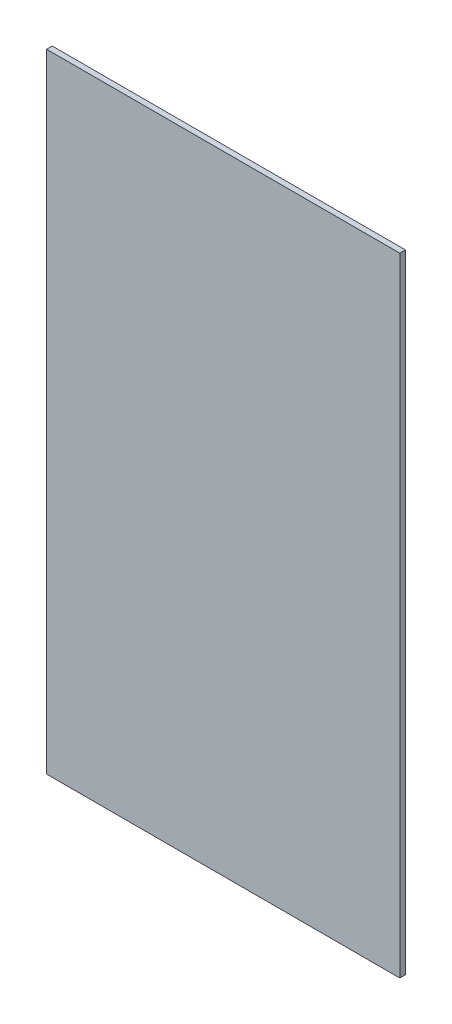
SolidWorks part; units mm, degrees
ref_plane "Front Plane" through (0, 0, 0) normal (0, 0, 1) x (1, 0, 0)
ref_plane "Top Plane" through (0, 0, 0) normal (0, 1, 0) x (1, 0, 0)
ref_plane "Right Plane" through (0, 0, 0) normal (1, 0, 0) x (0, 0, -1)
sketch "Sketch1" plane through (0, 0, 0) normal (0, 0, 1) x (1, 0, 0)
  line L1 (-27.8375, 672.8359) -> (370.6885, 672.8359)
  line L2 (-27.8375, 672.8359) -> (-27.8375, -35.5701)
  line L3 (-27.8375, -35.5701) -> (370.6885, -35.5701)
  line L4 (370.6885, 672.8359) -> (370.6885, -35.5701)
extrude "Boss-Extrude1" add sketch "Sketch1" along normal blind 6.35 contours L2 L1 L4 L3
